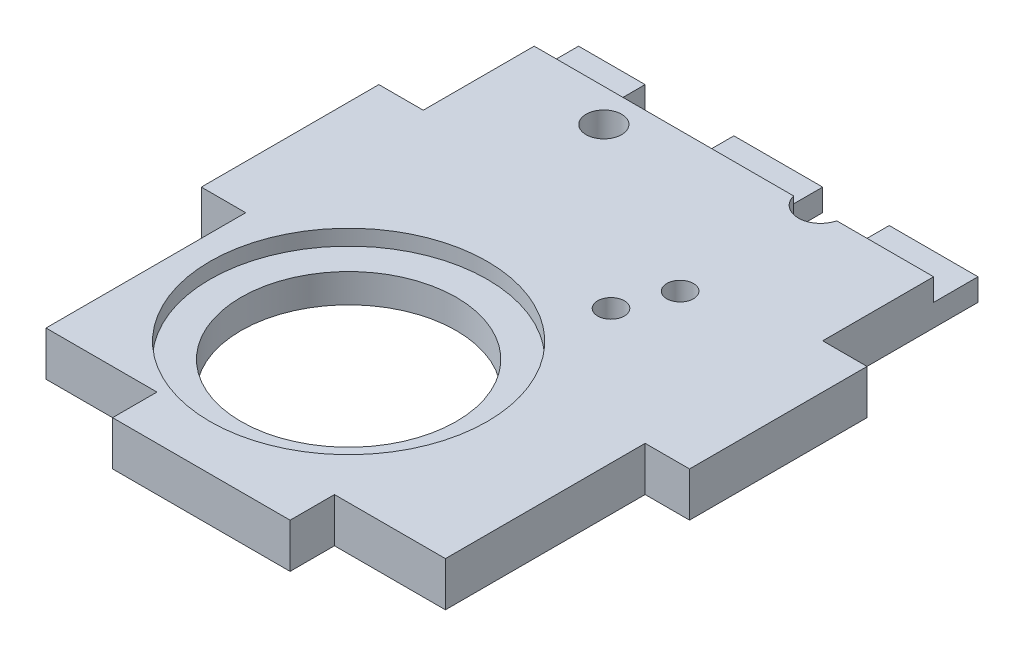
SolidWorks part; units mm, degrees
ref_plane "Front Plane" through (0, 0, 0) normal (0, 0, 1) x (1, 0, 0)
ref_plane "Top Plane" through (0, 0, 0) normal (0, 1, 0) x (1, 0, 0)
ref_plane "Right Plane" through (0, 0, 0) normal (1, 0, 0) x (0, 0, -1)
sketch "Sketch1" plane through (0, 0, 0) normal (0, 1, 0) x (1, 0, 0)
  line L1 (0, 0) -> (90, 0)
  line L2 (0, 0) -> (0, 110)
  line L3 (0, 110) -> (90, 110)
  line L4 (90, 0) -> (90, 110)
  line L5 (0, 85) -> (-10, 85)
  line L6 (0, 85) -> (0, 45)
  line L7 (0, 45) -> (-10, 45)
  line L8 (-10, 85) -> (-10, 45)
  line L9 (25, 110) -> (65, 110)
  line L13 (90, 85) -> (100, 85)
  line L14 (90, 85) -> (90, 45)
  line L15 (90, 45) -> (100, 45)
  line L16 (100, 85) -> (100, 45)
  line L17 (65, 0) -> (25, 0)
  line L18 (65, 0) -> (65, -10)
  line L19 (65, -10) -> (25, -10)
  line L20 (25, 0) -> (25, -10)
  point P23 (45, 0)
  point P24 (45, 110)
  dimension "D1" = 90
  dimension "D2" = 110
  dimension "D3" = 10
  dimension "D5" = 10
  dimension "D6" = 10
  dimension "D8" = 40
  dimension "D9" = 40
  dimension "D10" = 40
  dimension "D11" = 45
  dimension "D12" = 45
extrude "Boss-Extrude1" add sketch "Sketch1" along normal blind 10 contours L1 L4 L3 L2 | L5 L8 L7 L2 | L16 L13 L4 L15 | L1 L20 L19 L18
sketch "Sketch2" plane through (0, 10, 0) normal (0, 1, 0) x (1, 0, 0)
  line L0 (0, 102.57) -> (90.0901, 102.57) construction
  line L1 (65, 0) -> (90, 0) construction
  line L2 (23.1228, 98.57) -> (23.1228, 124.41) construction
  line L3 (-10, 85) -> (-10, 45) construction
  circle A0 centre (23.1228, 102.57) radius 4
  circle A1 centre (23.1228, 120.41) radius 4
  point P12 (0, 0)
  dimension "D2" = 8
  dimension "D4" = 8
  dimension "D1" = 102.57
  dimension "D3" = 25.84
  dimension "D5" = 33.1228
extrude "Cut-Extrude1" cut sketch "Sketch2" against normal through all
sketch "Sketch3" plane through (0, 10, 0) normal (0, 1, 0) x (1, 0, 0)
  line L0 (80.2934, 67.48) -> (5.633, 67.48)
  line L1 (65, 0) -> (90, 0) construction
  line L2 (58.7227, 64.6909) -> (65.352, 81.4257)
  circle A0 centre (59.8276, 67.48) radius 3
  circle A1 centre (64.2471, 78.6365) radius 3
  dimension "D2" = 6
  dimension "D4" = 6
  dimension "D1" = 67.48
  dimension "D3" = 18
extrude "Cut-Extrude2" cut sketch "Sketch3" against normal through all contours L2 A1 | L2 A1 | L0 A0 L2 | L2 A0 L0 | L0 A0 L2 | L2 A0 L0
sketch "Sketch4" plane through (0, 10, 0) normal (0, 1, 0) x (1, 0, 0)
  line L0 (0, 0) -> (0, 45) construction
  line L1 (65, 0) -> (90, 0) construction
  circle A0 centre (36.72, 31.47) radius 31.25
  dimension "D3" = 62.5
  dimension "D1" = 36.72
  dimension "D2" = 31.47
extrude "Cut-Extrude3" cut sketch "Sketch4" against normal blind 3.5
sketch "Sketch5" plane through (0, 6.5, 0) normal (0, 1, 0) x (1, 0, 0)
  circle A3 centre (36.72, 31.47) radius 24.25
  circle A4 centre (36.72, 31.47) radius 24.25
  dimension "D1" = 7
extrude "Cut-Extrude4" cut sketch "Sketch5" against normal through all
sketch "Sketch6" plane through (0, 10, 0) normal (0, 1, 0) x (1, 0, 0)
  line L1 (0, 110) -> (90, 110) construction
  circle A0 centre (63.3149, 111.2096) radius 5
  dimension "D1" = 10
  dimension "D2" = 26.6851
  dimension "D3" = 1.2096
extrude "Cut-Extrude5" cut sketch "Sketch6" against normal through all
sketch "Sketch8" plane through (0, 0, -110) normal (0, 0, -1) x (-1, 0, 0)
  line L1 (-90, 0) -> (-70, 0)
  line L2 (-90, 0) -> (-90, 5)
  line L3 (-90, 5) -> (-70, 5)
  line L4 (-70, 0) -> (-70, 5)
  line L6 (0, 0) -> (-15, 0)
  line L7 (0, 0) -> (0, 5)
  line L8 (0, 5) -> (-15, 5)
  line L9 (-15, 0) -> (-15, 5)
  line L10 (-55, 0) -> (-35, 0)
  line L11 (-55, 0) -> (-55, 5)
  line L12 (-55, 5) -> (-35, 5)
  line L13 (-35, 0) -> (-35, 5)
  dimension "D1" = 20
  dimension "D2" = 15
  dimension "D3" = 20
  dimension "D4" = 15
extrude "Boss-Extrude2" add sketch "Sketch8" along normal blind 10
